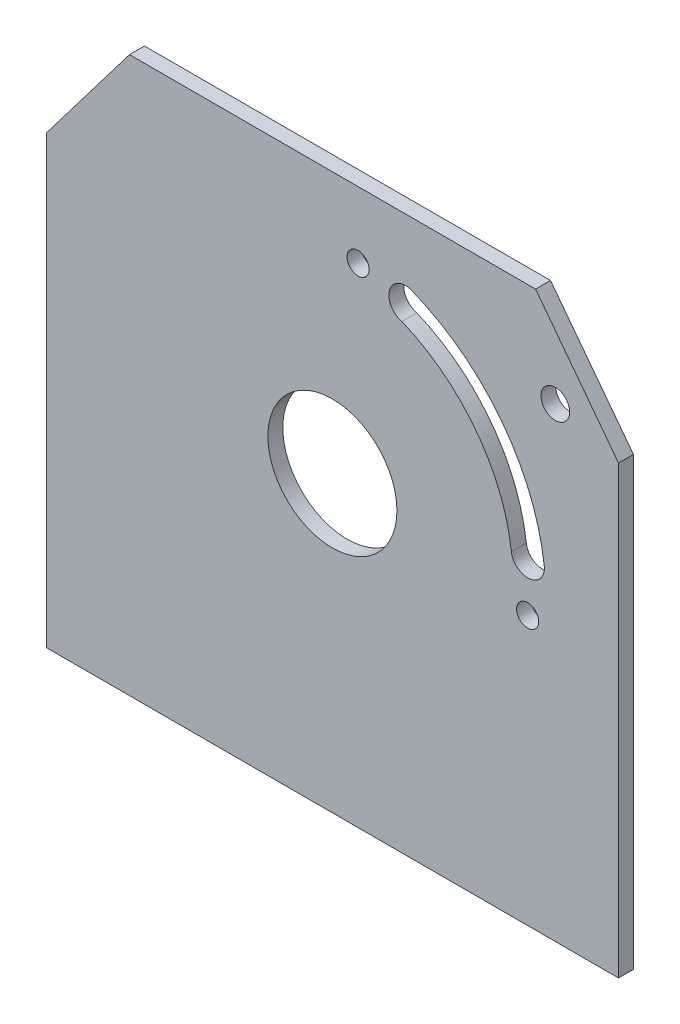
SolidWorks part; units mm, degrees
ref_plane "Front Plane" through (0, 0, 0) normal (0, 0, 1) x (1, 0, 0)
ref_plane "Top Plane" through (0, 0, 0) normal (0, 1, 0) x (1, 0, 0)
ref_plane "Right Plane" through (0, 0, 0) normal (1, 0, 0) x (0, 0, -1)
sketch "Sketch1" plane through (0, 0, 0) normal (0, 0, 1) x (1, 0, 0)
  line L0 (122.0182, 78.9322) -> (103.6651, 103.0902)
  line L1 (-4.5387, -19.7473) -> (122.0182, -19.7473)
  line L2 (-4.5387, 78.9322) -> (13.8145, 103.0902)
  line L3 (-4.5387, -19.7473) -> (-4.5387, 78.9322)
  line L4 (122.0182, -19.7473) -> (122.0182, 78.9322)
  line L5 (58.7102, 45.2839) -> (108.0314, 83.2746) construction
  line L6 (13.8145, 103.0902) -> (103.6651, 103.0902)
  line L7 (25.2805, 88.6839) -> (58.7102, 45.2839) construction
  line L8 (58.7102, 45.2839) -> (126.6162, 45.2839) construction
  circle A0 centre (58.7102, 45.2839) radius 14.2802
  arc A1 (105.5849, 50.9789) -> (76.2585, 89.1214) centre (58.7102, 45.2839) ccw
  arc A2 (76.2585, 89.1214) -> (74.0707, 82.0997) centre (74.8907, 85.6959) ccw
  arc A3 (98.3115, 50.0887) -> (105.5849, 50.9789) centre (101.9482, 50.5338) ccw
  arc A4 (98.3115, 50.0887) -> (74.0707, 82.0997) centre (58.7102, 45.2839) ccw
  circle A5 centre (108.0314, 83.2746) radius 3.175
  circle A7 centre (64.386, 88.4087) radius 2.4459
  circle A8 centre (101.9144, 39.6877) radius 2.4459
  point P23 (58.7398, -19.7473)
  dimension "D1" = 127.606
extrude "Extrude1" add sketch "Sketch1" along normal blind 3.302
ref_plane "Plane2" through (-12.3952, -9.549, 0) normal (0.7922, 0.6103, 0) x (-0.6103, 0.7922, 0)
ref_plane "Plane3" through (58.7366, 45.2496, 0) normal (0.7922, 0.6103, 0) x (0, 0, -1)
ref_plane "Plane4" through (0, 0, 3.302) normal (0, 0, 1) x (1, 0, 0)
